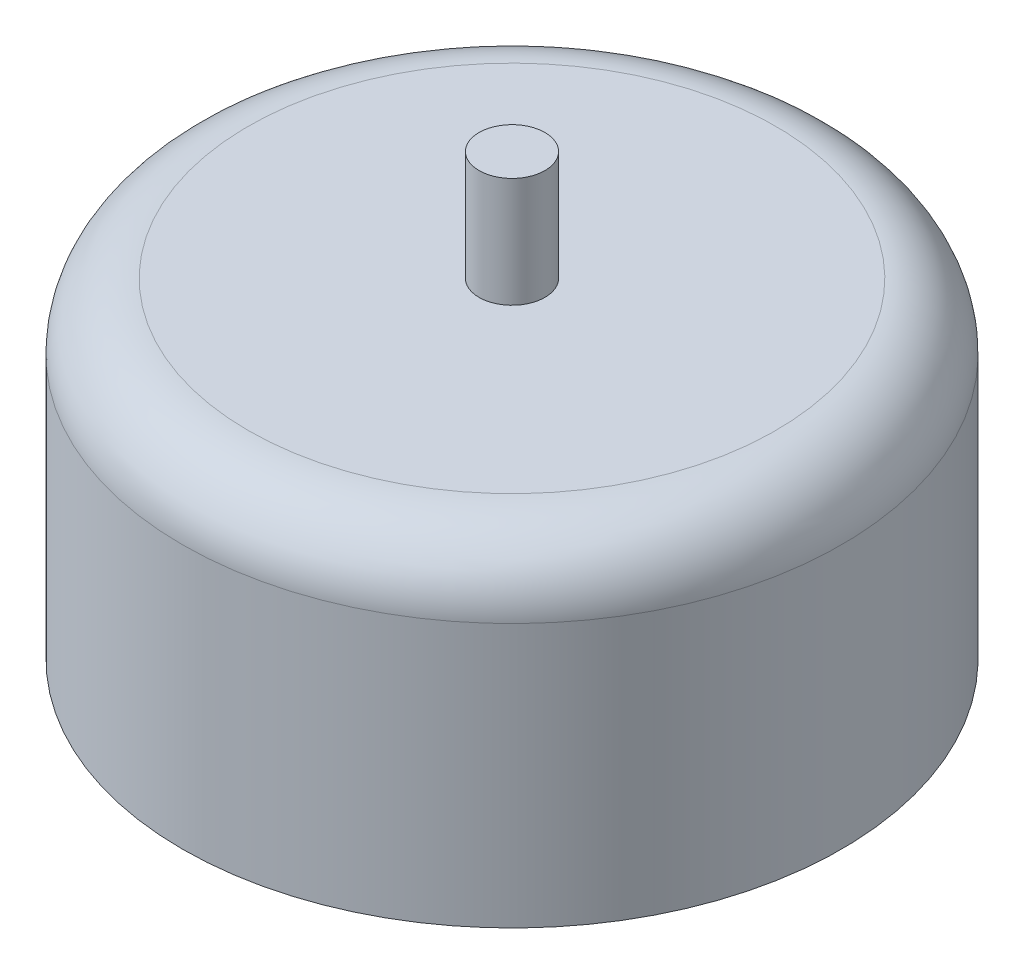
SolidWorks part; units mm, degrees
ref_plane "前视基准面" through (0, 0, 0) normal (0, 0, 1) x (1, 0, 0)
ref_plane "上视基准面" through (0, 0, 0) normal (0, 1, 0) x (1, 0, 0)
ref_plane "右视基准面" through (0, 0, 0) normal (1, 0, 0) x (0, 0, -1)
sketch "草图2" plane through (0, 0, 0) normal (0, 1, 0) x (1, 0, 0)
  circle A0 centre (0, 0) radius 15
  dimension "D1" = 30
extrude "凸台-拉伸1" add sketch "草图2" along normal blind 15
sketch "草图3" plane through (0, 15, 0) normal (0, 1, 0) x (1, 0, 0)
  circle A0 centre (0, 0) radius 1.5
  dimension "D1" = 3
fillet "圆角1" radius 3 1 edges at (0, 15, 15)
extrude "凸台-拉伸2" add sketch "草图3" along normal blind 5 contours A0
sketch "草图4" plane through (0, 0, 0) normal (0, -1, 0) x (1, 0, 0)
  line L1 (-5, 5) -> (5, 5) construction
  line L2 (-5, 5) -> (-5, -5) construction
  line L3 (-5, -5) -> (5, -5) construction
  line L4 (5, 5) -> (5, -5) construction
  line L5 (-5, 5) -> (5, -5) construction
  line L6 (-5, -5) -> (5, 5) construction
  circle A0 centre (0, 5) radius 1.5
  circle A1 centre (-5, 0) radius 1.5
  circle A2 centre (5, 0) radius 1.5
  circle A3 centre (0, -5) radius 1.5
  point P0 (0, 0)
  dimension "D2" = 3
  dimension "D1" = 10
extrude "凸台-拉伸3" add sketch "草图4" along normal blind 2
